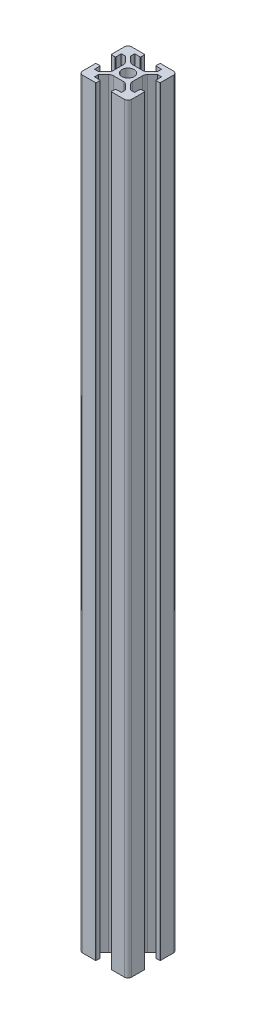
SolidWorks part; units mm, degrees
ref_plane "Front Plane" through (0, 0, 0) normal (0, 0, 1) x (1, 0, 0)
ref_plane "Top Plane" through (0, 0, 0) normal (0, 1, 0) x (1, 0, 0)
ref_plane "Right Plane" through (0, 0, 0) normal (1, 0, 0) x (0, 0, -1)
sketch "Sketch1" plane through (0, 0, 0) normal (0, 1, 0) x (1, 0, 0)
  line L0 (10, 20) -> (10, 10) construction
  line L1 (0, 0) -> (20, 0)
  line L2 (0, 0) -> (0, 20)
  line L3 (0, 20) -> (20, 20)
  line L4 (20, 0) -> (20, 20)
  line L5 (6.1, 13.9) -> (13.9, 13.9)
  line L6 (6.1, 13.9) -> (6.1, 6.1)
  line L7 (6.1, 6.1) -> (13.9, 6.1)
  line L8 (13.9, 13.9) -> (13.9, 6.1)
  line L9 (10, 10) -> (0, 10) construction
  line L10 (2.8607, 18.2) -> (18.2, 2.8607)
  line L11 (1.8, 18.2) -> (18.2, 18.2)
  line L12 (1.8, 18.2) -> (1.8, 1.8)
  line L13 (1.8, 1.8) -> (18.2, 1.8)
  line L14 (18.2, 18.2) -> (18.2, 1.8)
  line L15 (1.8, 17.1393) -> (17.1393, 1.8)
  line L16 (17.1393, 18.2) -> (1.8, 2.8607)
  line L17 (18.2, 17.1393) -> (2.8607, 1.8)
  line L18 (1.8, 18.2) -> (18.2, 1.8) construction
  line L19 (1.8, 17.1393) -> (2.3303, 17.6697) construction
  line L20 (2.3303, 17.6697) -> (2.8607, 18.2) construction
  line L21 (1.8, 1.8) -> (18.2, 18.2) construction
  line L24 (18.2, 4.5) -> (15.5, 4.5)
  line L25 (15.5, 1.8) -> (15.5, 4.5)
  line L26 (18.2, 13.1) -> (20, 13.1)
  line L29 (18.2, 15.5) -> (15.5, 15.5)
  line L30 (15.5, 18.2) -> (15.5, 15.5)
  line L31 (18.2, 6.9) -> (20, 6.9)
  line L32 (4.5, 18.2) -> (4.5, 15.5)
  line L33 (1.8, 15.5) -> (4.5, 15.5)
  line L34 (4.5, 1.8) -> (4.5, 4.5)
  line L35 (1.8, 4.5) -> (4.5, 4.5)
  line L36 (1.8, 6.9) -> (0, 6.9)
  line L37 (1.8, 13.1) -> (0, 13.1)
  line L38 (6.9, 20) -> (6.9, 18.2)
  line L39 (13.1, 20) -> (13.1, 18.2)
  line L40 (6.9, 0) -> (6.9, 1.8)
  line L41 (13.1, 0) -> (13.1, 1.8)
  circle A0 centre (10, 10) radius 2.5
  point P9 (10, 20)
  point P10 (10, 13.9)
  point P11 (0, 10)
  point P12 (6.1, 10)
  point P21 (10, 18.2)
  point P22 (1.8, 10)
  dimension "D3" = 5
  dimension "D1" = 20
  dimension "D2" = 6.1
  dimension "D4" = 1.5
  dimension "D5" = 1.5
  dimension "D6" = 1.8
  dimension "D7" = 11
  dimension "D8" = 6.2
  dimension "D9" = 6.9
  dimension "D10" = 6.2
  dimension "D11" = 6.9
extrude "Boss-Extrude1" add sketch "Sketch1" along normal blind 330 contours L38 L3 L2 L37 L12 L11 | L15 L33 L32 L10 L11 L12 | L32 L11 L10 | L12 L33 L15 | L33 L15 L6 L5 L10 L32 | L3 L39 L11 L14 L26 L4 | L11 L30 L16 | L16 L30 L29 L17 L14 L11 | L29 L14 L17 | L30 L16 L5 L8 L17 L29 | A0 L16 L5 L10 | A0 L10 L5 L6 L15 | A0 L17 L8 L5 L16 | A0 L10 L8 L17 | A0 L15 L6 L16 | A0 L16 L6 L7 L17 | A0 L17 L7 L15 | A0 L15 L7 L8 L10 | L16 L35 L34 L17 L7 L6 | L15 L25 L24 L10 L8 L7 | L35 L12 L16 | L35 L16 L12 L13 L17 L34 | L13 L34 L17 | L1 L40 L13 L12 L36 L2 | L14 L24 L10 | L25 L15 L13 L14 L10 L24 | L25 L13 L15 | L41 L1 L4 L31 L14 L13
fillet "Fillet1" radius 1.5 4 edges at (0, 165, -20) (0, 165, 0) (20, 165, -20) (20, 165, 0)
fillet "Fillet2" radius 0.2 32 edges at (6.9, 165, -1.8) (6.9, 165, 0) (0, 165, -6.9) (1.8, 165, -6.9) (1.8, 165, -4.5) (3.4393, 165, -4.5) (3.4393, 165, -15.5) (1.8, 165, -15.5) (1.8, 165, -13.1) (0, 165, -13.1) (6.9, 165, -20) (6.9, 165, -18.2) (4.5, 165, -18.2) (4.5, 165, -16.5607) (15.5, 165, -16.5607) (15.5, 165, -18.2) (13.1, 165, -18.2) (13.1, 165, -20) (20, 165, -13.1) (18.2, 165, -13.1) (18.2, 165, -15.5) (16.5607, 165, -15.5) (16.5607, 165, -4.5) (18.2, 165, -4.5) (18.2, 165, -6.9) (20, 165, -6.9) (13.1, 165, 0) (13.1, 165, -1.8) (15.5, 165, -1.8) (15.5, 165, -3.4393) (4.5, 165, -3.4393) (4.5, 165, -1.8)
fillet "Fillet3" radius 2 8 edges at (13.9, 165, -7.1607) (12.8393, 165, -6.1) (7.1607, 165, -6.1) (6.1, 165, -12.8393) (6.1, 165, -7.1607) (12.8393, 165, -13.9) (7.1607, 165, -13.9) (13.9, 165, -12.8393)
sketch "Sketch2" plane through (0, 0, -20) normal (0, 0, -1) x (-1, 0, 0)
  line L0 (-10, 330) -> (-10, 0) construction
  line L1 (-7.9891, 330) -> (-12.0109, 330) construction
  line L2 (-7.9891, 0) -> (-12.0109, 0) construction
  circle A0 centre (-10, 297) radius 2.1
  circle A1 centre (-10, 254) radius 2.1
  circle A2 centre (-10, 53) radius 2.1
  circle A3 centre (-10, 10) radius 2.1
  dimension "D3" = 4.2
  dimension "D1" = 43
  dimension "D2" = 33
  dimension "D4" = 10
  dimension "D5" = 43
extrude "Cut-Extrude1" cut sketch "Sketch2" against normal through all
sketch "Sketch5" plane through (0, 330, 0) normal (0, 1, 0) x (1, 0, 0)
  line L1 (-1.0132, 20.5994) -> (21.0588, 20.5994)
  line L2 (-1.0132, 20.5994) -> (-1.0132, -0.3356)
  line L3 (-1.0132, -0.3356) -> (21.0588, -0.3356)
  line L4 (21.0588, 20.5994) -> (21.0588, -0.3356)
  point P4 (-1.0132, 20.5994)
extrude "Cut-Extrude3" cut sketch "Sketch5" against normal blind 20
